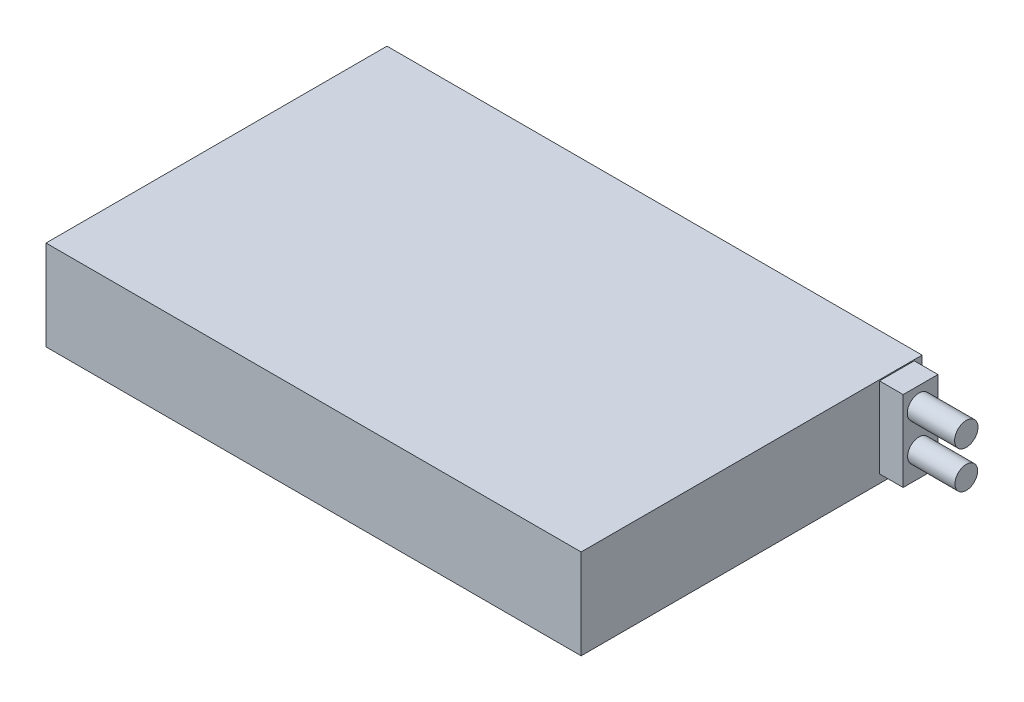
SolidWorks part; units mm, degrees
ref_plane "前视基准面" through (0, 0, 0) normal (0, 0, 1) x (1, 0, 0)
ref_plane "上视基准面" through (0, 0, 0) normal (0, 1, 0) x (1, 0, 0)
ref_plane "右视基准面" through (0, 0, 0) normal (1, 0, 0) x (0, 0, -1)
sketch "草图1" plane through (0, 0, 0) normal (0, 1, 0) x (1, 0, 0)
  line L1 (0, 0) -> (113, 0)
  line L2 (0, 0) -> (0, -72)
  line L3 (0, -72) -> (113, -72)
  line L4 (113, 0) -> (113, -72)
  dimension "D1" = 113
  dimension "D2" = 72
extrude "凸台-拉伸1" add sketch "草图1" along normal blind 19
sketch "草图2" plane through (113, 0, 0) normal (1, 0, 0) x (0, 0, -1)
  line L1 (-9.0018, 18.7825) -> (-1.6577, 18.7825)
  line L2 (-9.0018, 18.7825) -> (-9.0018, 1.7806)
  line L3 (-9.0018, 1.7806) -> (-1.6577, 1.7806)
  line L4 (-1.6577, 18.7825) -> (-1.6577, 1.7806)
extrude "凸台-拉伸2" add sketch "草图2" along normal blind 5
sketch "草图3" plane through (118, 0, 0) normal (1, 0, 0) x (0, 0, -1)
  circle A0 centre (-5.6723, 14.9276) radius 2.4719
  circle A1 centre (-5.6723, 6.9781) radius 2.3957
extrude "凸台-拉伸3" add sketch "草图3" along normal blind 10
